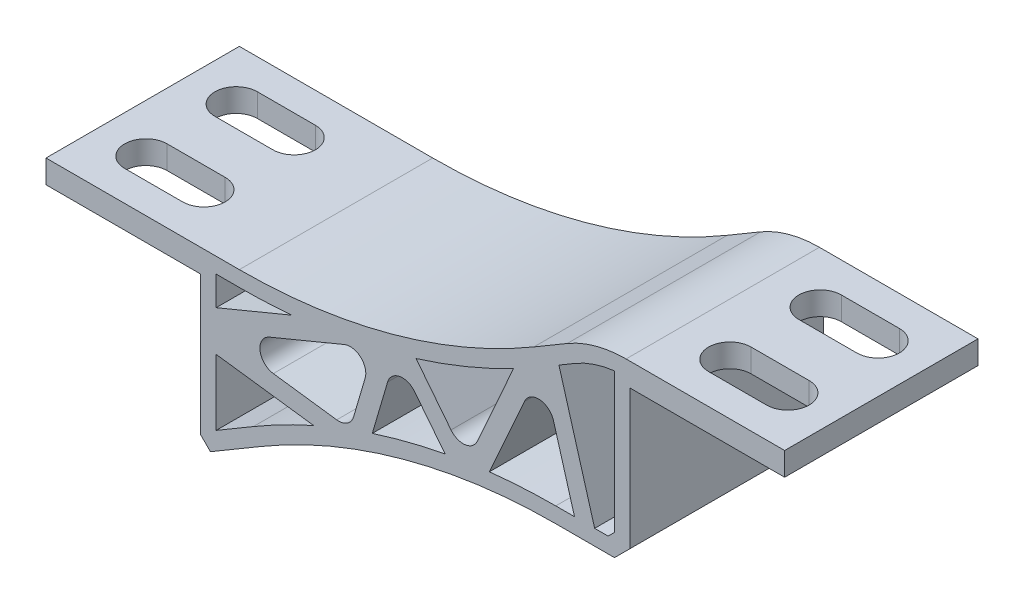
SolidWorks part; units mm, degrees
ref_plane "Front Plane" through (0, 0, 0) normal (0, 0, 1) x (1, 0, 0)
ref_plane "Top Plane" through (0, 0, 0) normal (0, 1, 0) x (1, 0, 0)
ref_plane "Right Plane" through (0, 0, 0) normal (1, 0, 0) x (0, 0, -1)
sketch "Sketch1" plane through (0, 0, 0) normal (0, 0, 1) x (1, 0, 0)
  line L0 (0, 0) -> (0, 3)
  line L1 (70.9091, 18) -> (95.5, 18)
  line L2 (95.5, 18) -> (95.5, 15)
  line L3 (95.5, 15) -> (75.5, 15)
  line L4 (75.5, 15) -> (75.5, -5)
  line L5 (75.5, -5) -> (45.4545, -5)
  line L8 (45.4545, -5) -> (20, -20)
  line L9 (20, -20) -> (20, 0)
  line L11 (0, 3) -> (45.4545, 3)
  line L12 (20, 0) -> (0, 0)
  line L14 (45.4545, 3) -> (70.9091, 18)
  point P14 (45.4545, -5)
  dimension "D1" = 20
  dimension "D2" = 20
  dimension "D3" = 20
  dimension "D4" = 3
  dimension "D5" = 55.5
  dimension "D6" = 25.4545
  dimension "D7" = 20
  dimension "D8" = 3
  dimension "D9" = 8
extrude "Boss-Extrude1" add sketch "Sketch1" along normal blind 25
sketch "Sketch3" plane through (0, 3, 0) normal (0, 1, 0) x (1, 0, 0)
  line L0 (20, 0) -> (20, -25) construction
  line L1 (0, 0) -> (45.4545, 0) construction
  line L2 (0, -25) -> (45.4545, -25) construction
  line L3 (75.5, 0) -> (75.5, -25) construction
  line L4 (70.9091, 0) -> (95.5, 0) construction
  line L5 (70.9091, -25) -> (95.5, -25) construction
  line L6 (95.5, -25) -> (95.5, 0) construction
  line L7 (0, -25) -> (0, 0) construction
  line L8 (6.25, -6.6667) -> (13.75, -6.6667) construction
  line L9 (6.25, -3.9167) -> (13.75, -3.9167)
  line L10 (6.25, -9.4167) -> (13.75, -9.4167)
  line L11 (6.25, -18.3333) -> (13.75, -18.3333) construction
  line L12 (6.25, -15.5833) -> (13.75, -15.5833)
  line L13 (6.25, -21.0833) -> (13.75, -21.0833)
  line L14 (81.75, -6.6667) -> (89.25, -6.6667) construction
  line L15 (81.75, -3.9167) -> (89.25, -3.9167)
  line L16 (81.75, -9.4167) -> (89.25, -9.4167)
  line L17 (81.75, -18.3333) -> (89.25, -18.3333) construction
  line L18 (81.75, -15.5833) -> (89.25, -15.5833)
  line L19 (81.75, -21.0833) -> (89.25, -21.0833)
  line L20 (0, -12.5) -> (95.5, -12.5) construction
  arc A0 (6.25, -3.9167) -> (6.25, -9.4167) centre (6.25, -6.6667) ccw
  arc A1 (13.75, -9.4167) -> (13.75, -3.9167) centre (13.75, -6.6667) ccw
  arc A2 (6.25, -15.5833) -> (6.25, -21.0833) centre (6.25, -18.3333) ccw
  arc A3 (13.75, -21.0833) -> (13.75, -15.5833) centre (13.75, -18.3333) ccw
  arc A4 (81.75, -3.9167) -> (81.75, -9.4167) centre (81.75, -6.6667) ccw
  arc A5 (89.25, -9.4167) -> (89.25, -3.9167) centre (89.25, -6.6667) ccw
  arc A6 (81.75, -15.5833) -> (81.75, -21.0833) centre (81.75, -18.3333) ccw
  arc A7 (89.25, -21.0833) -> (89.25, -15.5833) centre (89.25, -18.3333) ccw
  point P18 (10, -6.6667)
  point P23 (10, -18.3333)
  point P30 (85.5, -6.6667)
  point P37 (85.5, -18.3333)
  dimension "D1" = 20
  dimension "D2" = 20
  dimension "D3" = 5.5
  dimension "D4" = 10
  dimension "D5" = 10
  dimension "D6" = 7.5
  dimension "D7" = 6.6667
extrude "Cut-Extrude2" cut sketch "Sketch3" against normal through all both and the other way through all
fillet "Fillet2" radius 75 2 edges at (45.4545, -5, 12.5) (45.4545, 3, 12.5)
fillet "Fillet3" radius 15 1 edges at (70.9091, 18, 12.5)
chamfer "Chamfer2" distance 2 angle 45 1 edges at (75.5, -5, 12.5)
chamfer "Chamfer3" distance 2 angle 45 1 edges at (20, -20, 12.5)
sketch "Sketch4" plane through (0, 0, 25) normal (0, 0, 1) x (1, 0, 0)
  line L39 (64.0923, 11.6615) -> (68.3336, -3)
  line L40 (66.3158, 12.9718) -> (70.9361, -3)
  line L41 (25, -7.75) -> (31.0404, -7.75) construction
  line L52 (31.8062, 1.3014) -> (22, -2.7604)
  line L53 (42.4451, 3.0022) -> (22, -5.4664)
  line L54 (22, -5.4664) -> (39.2832, -7.75)
  line L55 (22, -7.9882) -> (34.5996, -9.6529)
  line L56 (42.1843, -6.7461) -> (45.26, 3.7132)
  line L57 (42.4451, 3.0022) -> (39.2832, -7.75)
  line L58 (45.26, 3.7132) -> (51.6052, -4.3402)
  line L59 (47.8481, 4.4679) -> (54.412, -3.8632)
  line L60 (54.412, -3.8632) -> (60.4532, 9.6474)
  line L61 (57.3217, -3.4803) -> (64.0923, 11.6615)
  line L65 (22, 1) -> (22, -16.5)
  line L66 (22, -16.5) -> (26.8168, -13.6615)
  line L67 (65.9091, -3) -> (72.6716, -3)
  line L68 (72.6716, -3) -> (73.5, -2.1716)
  line L69 (73.5, -2.1716) -> (73.5, 15.9132)
  line L70 (68.4, 14.2) -> (64.0923, 11.6615)
  line L71 (25, 1) -> (22, 1)
  line L72 (22, 1) -> (22, -16.5)
  line L73 (22, -16.5) -> (26.8168, -13.6615)
  line L74 (65.9091, -3) -> (72.6716, -3)
  line L75 (72.6716, -3) -> (73.5, -2.1716)
  line L76 (73.5, -2.1716) -> (73.5, 15.9132)
  line L77 (68.4, 14.2) -> (64.0923, 11.6615)
  line L78 (25, 1) -> (22, 1)
  arc A12 (65.9091, -3) -> (26.8168, -13.6615) centre (65.9091, -80) ccw
  arc A13 (73.5, 15.9132) -> (68.4, 14.2) centre (75, 3) ccw
  arc A14 (25, 1) -> (64.0923, 11.6615) centre (25, 78) ccw
  arc A15 (65.9091, -3) -> (26.8168, -13.6615) centre (65.9091, -80) ccw
  arc A16 (73.5, 15.9132) -> (68.4, 14.2) centre (75, 3) ccw
  arc A17 (25, 1) -> (64.0923, 11.6615) centre (25, 78) ccw
  point P2 (38.697, -7.75)
  point P4 (42.1843, 3.0022)
  point P31 (22, -7.75)
  dimension "D3" = 22.5
  dimension "D4" = 2.5
  dimension "D5" = 2.5
  dimension "D6" = 2.5
  dimension "D7" = 2.5
  dimension "D8" = 2.5
  dimension "D9" = 2.5
  dimension "D1" = 2
extrude "Cut-Extrude3" cut sketch "Sketch4" against normal through all both and the other way through all contours A17 L78 L72 L52 | L57 L53 L54 | A15 L55 L72 L73 | A15 L58 L56 | A17 L59 L60 | A15 L74 L39 L61 | L76 A16 L77 L40 L74 L75
fillet "Fillet4" radius 2 6 edges at (22, -5.4664, 12.5) (64.0923, 11.6615, 12.5) (54.412, -3.8632, 12.5) (45.26, 3.7132, 12.5) (42.4451, 3.0022, 12.5) (39.2832, -7.75, 12.5)
